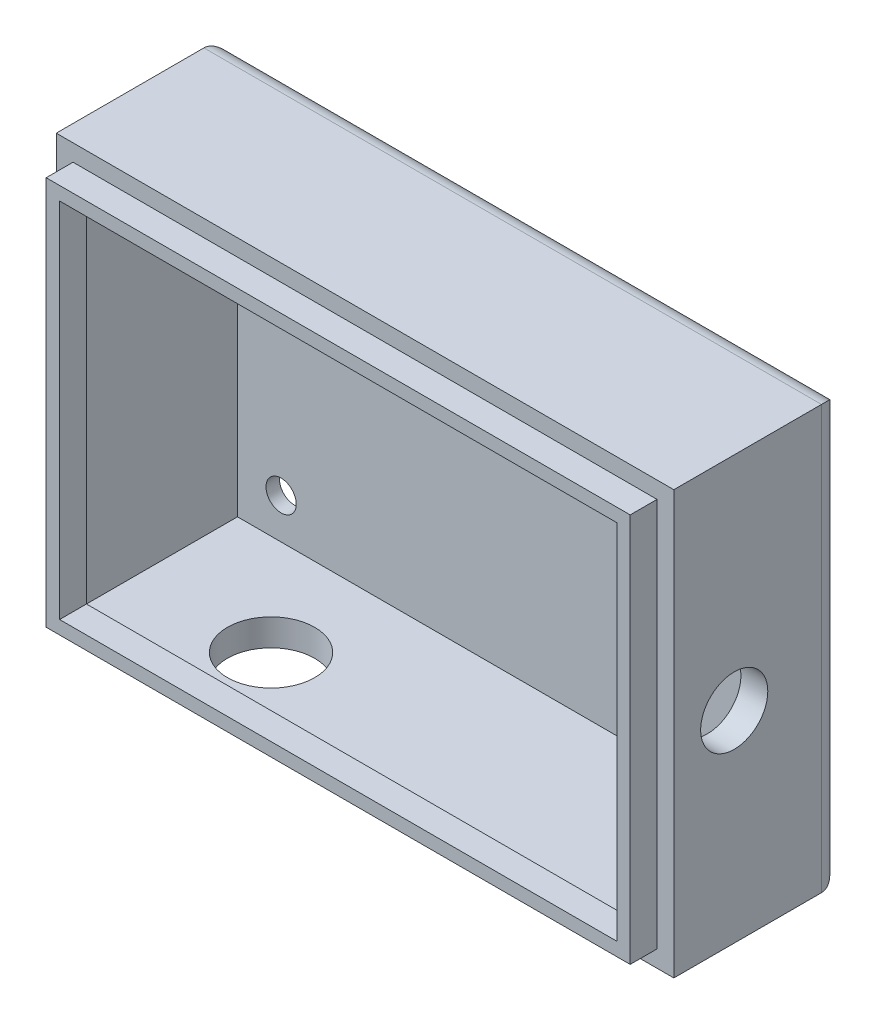
SolidWorks part; units mm, degrees
ref_plane "Front Plane" through (0, 0, 0) normal (0, 0, 1) x (1, 0, 0)
ref_plane "Top Plane" through (0, 0, 0) normal (0, 1, 0) x (1, 0, 0)
ref_plane "Right Plane" through (0, 0, 0) normal (1, 0, 0) x (0, 0, -1)
sketch "Sketch3" plane through (0, 0, 0) normal (0, 0, 1) x (1, 0, 0)
  line L1 (0, 0) -> (92, 0)
  line L2 (0, 0) -> (0, 63)
  line L3 (0, 63) -> (92, 63)
  line L4 (92, 0) -> (92, 63)
  line L5 (8, 55.5) -> (84.5, 55.5)
  line L6 (8, 55.5) -> (8, 7.5)
  line L7 (8, 7.5) -> (84.5, 7.5)
  line L8 (84.5, 55.5) -> (84.5, 7.5)
  circle A4 centre (82, 53) radius 2.25
  circle A5 centre (82, 10) radius 2.25
  circle A6 centre (10.5, 10) radius 2.25
  circle A7 centre (10.5, 53) radius 2.25
  point P9 (0, 0)
  dimension "D23" = 4.5
  dimension "D24" = 4.5
  dimension "D25" = 4.5
  dimension "D26" = 4.5
  dimension "D1" = 63
  dimension "D2" = 92
  dimension "D3" = 48
  dimension "D4" = 76.5
  dimension "D5" = 7.5
  dimension "D6" = 8
  dimension "D8" = 7.5
  dimension "D27" = 2.5
  dimension "D28" = 2.5
  dimension "D29" = 2.5
  dimension "D30" = 2.5
  dimension "D31" = 2.5
  dimension "D32" = 2.5
  dimension "D33" = 2.5
  dimension "D34" = 2.5
extrude "Boss-Extrude3" add sketch "Sketch3" along normal blind 25
sketch "Sketch4" plane through (0, 0, 25) normal (0, 0, 1) x (1, 0, 0)
  line L0 (0, 0) -> (0, 63) construction
  line L1 (4, 59) -> (88, 59)
  line L2 (4, 59) -> (4, 4)
  line L3 (4, 4) -> (88, 4)
  line L4 (88, 59) -> (88, 4)
  line L5 (0, 0) -> (92, 0) construction
  line L6 (0, 63) -> (92, 63) construction
  line L7 (92, 0) -> (92, 63) construction
  dimension "D1" = 4
  dimension "D2" = 4
  dimension "D3" = 4
  dimension "D4" = 4
extrude "Cut-Extrude1" cut sketch "Sketch4" against normal blind 23 contours L2 L1 L4 L3
sketch "Sketch5" plane through (0, 0, 25) normal (0, 0, 1) x (1, 0, 0)
  line L0 (0, 0) -> (0, 63) construction
  line L1 (2.5, 60.5) -> (89.5, 60.5)
  line L2 (2.5, 60.5) -> (2.5, 2.5)
  line L3 (2.5, 2.5) -> (89.5, 2.5)
  line L4 (89.5, 60.5) -> (89.5, 2.5)
  line L5 (0, 63) -> (92, 63) construction
  line L6 (92, 0) -> (92, 63) construction
  line L7 (0, 0) -> (92, 0) construction
  point P4 (78.9839, 6.4618)
  point P5 (8.5481, 22.8511)
  dimension "D1" = 2.5
  dimension "D2" = 2.5
  dimension "D3" = 2.5
  dimension "D4" = 2.5
fillet "Fillet1" radius 3 4 edges at (46, 0, 0) (0, 31.5, 0) (46, 63, 0) (92, 31.5, 0)
sketch "Sketch6" plane through (0, 0, 0) normal (-1, 0, 0) x (0, 0, 1)
  line L0 (25, 0) -> (3, 0) construction
  line L1 (22, 18) -> (7, 18)
  line L2 (22, 18) -> (22, 39)
  line L3 (22, 39) -> (7, 39)
  line L4 (7, 18) -> (7, 39)
  line L5 (25, 0) -> (25, 63) construction
  point P4 (-8.5916, 31.5221)
  dimension "D1" = 18
  dimension "D2" = 21
  dimension "D3" = 15
  dimension "D4" = 3
extrude "Boss-Extrude4" add sketch "Sketch5" along normal blind 4
sketch "Sketch7" plane through (0, 0, 29) normal (0, 0, 1) x (1, 0, 0)
  line L0 (89.5, 2.5) -> (89.5, 60.5) construction
  line L1 (4.5, 4.5) -> (87.5, 4.5)
  line L2 (4.5, 4.5) -> (4.5, 58.5)
  line L3 (4.5, 58.5) -> (87.5, 58.5)
  line L4 (87.5, 4.5) -> (87.5, 58.5)
  line L5 (89.5, 60.5) -> (2.5, 60.5) construction
  line L6 (2.5, 2.5) -> (89.5, 2.5) construction
  line L7 (2.5, 60.5) -> (2.5, 2.5) construction
  dimension "D1" = 2
  dimension "D2" = 2
  dimension "D3" = 2
  dimension "D4" = 2
extrude "Cut-Extrude4" cut sketch "Sketch7" against normal blind 27
sketch "Sketch9" plane through (0, 0, 0) normal (0, -1, 0) x (1, 0, 0)
  line L0 (0, 25) -> (92, 25) construction
  line L1 (0, 25) -> (0, 3) construction
  circle A0 centre (24, 17) radius 6.5
  dimension "D1" = 13
  dimension "D2" = 8
  dimension "D3" = 24
extrude "Cut-Extrude6" cut sketch "Sketch9" against normal blind 27
sketch "Sketch11" plane through (92, 0, 0) normal (1, 0, 0) x (0, 0, -1)
  line L0 (-25, 0) -> (-3, 0) construction
  line L1 (-25, 0) -> (-25, 63) construction
  circle A0 centre (-16, 30) radius 5
  point P2 (0, 0)
  dimension "D1" = 10
  dimension "D2" = 30
  dimension "D3" = 9
extrude "Cut-Extrude7" cut sketch "Sketch11" against normal blind 27
